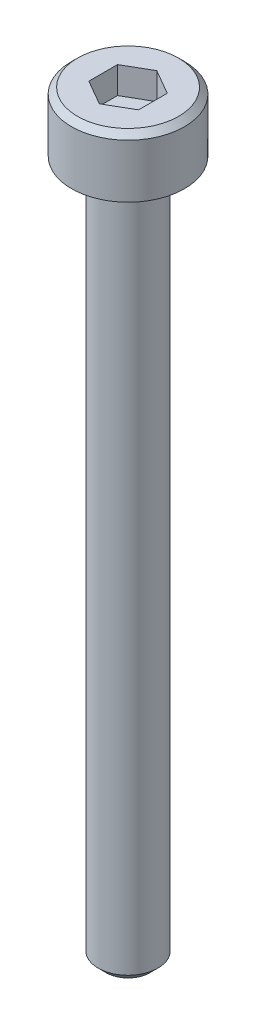
SolidWorks part; units mm, degrees
ref_plane "Front Plane" through (0, 0, 0) normal (0, 0, 1) x (1, 0, 0)
ref_plane "Top Plane" through (0, 0, 0) normal (0, 1, 0) x (1, 0, 0)
ref_plane "Right Plane" through (0, 0, 0) normal (1, 0, 0) x (0, 0, -1)
sketch "Sketch1" plane through (0, 0, 0) normal (0, 0, 1) x (1, 0, 0)
  line L0 (0, -35) -> (1.1, -35)
  line L1 (1.1, -35) -> (1.5, -34.6)
  line L2 (1.5, -34.6) -> (1.5, 0)
  line L3 (1.5, 0) -> (2.84, 0)
  line L4 (2.84, 0) -> (2.84, 2.7)
  line L5 (2.84, 2.7) -> (2.54, 3)
  line L6 (2.54, 3) -> (0, 3)
  line L7 (0, 3) -> (0, -35)
  line L8 (0, -10) -> (0, 1000) construction
revolve "Revolve1" add sketch "Sketch1" angle 360 about L8
cosmetic thread "Cosmetic Thread1"
ref_plane "Plane1" through (0, 3, 0) normal (0, 1, 0) x (1, 0, 0)
sketch "Sketch2" plane through (0, 3, 0) normal (0, 1, 0) x (1, 0, 0)
  line L0 (1.25, -0.7217) -> (0, -1.4434)
  line L1 (0, -1.4434) -> (-1.25, -0.7217)
  line L2 (-1.25, -0.7217) -> (-1.25, 0.7217)
  line L3 (-1.25, 0.7217) -> (0, 1.4434)
  line L4 (0, 1.4434) -> (1.25, 0.7217)
  line L5 (1.25, 0.7217) -> (1.25, -0.7217)
extrude "Cut-Extrude1" cut sketch "Sketch2" against normal blind 1.35
